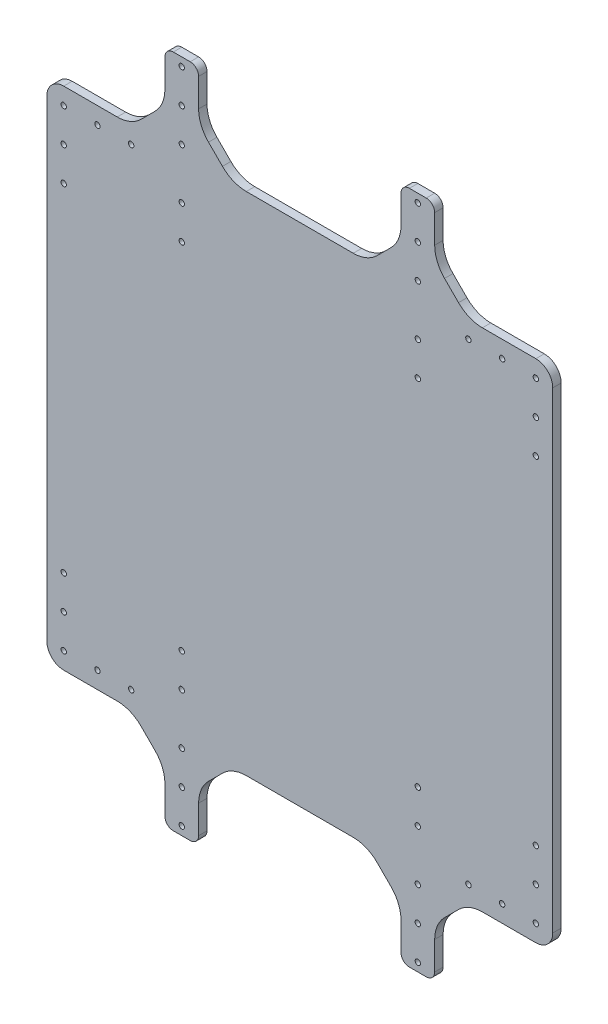
SolidWorks part; units mm, degrees
material "Thornel Mat VMA"
ref_plane "前视基准面" through (0, 0, 0) normal (0, 0, 1) x (1, 0, 0)
ref_plane "上视基准面" through (0, 0, 0) normal (0, 1, 0) x (1, 0, 0)
ref_plane "右视基准面" through (0, 0, 0) normal (1, 0, 0) x (0, 0, -1)
other "Configuration Table"
sketch "草图1" plane through (0, 0, 0) normal (0, 0, 1) x (1, 0, 0)
  line L1 (0, 0) -> (300, 0)
  line L2 (0, 0) -> (0, 300)
  line L3 (0, 300) -> (300, 300)
  line L4 (300, 0) -> (300, 300)
  dimension "D1" = 300
  dimension "D2" = 300
extrude "凸台-拉伸1" add sketch "草图1" along normal blind 5
sketch "草图2" plane through (0, 0, 5) normal (0, 0, 1) x (1, 0, 0)
  line L0 (300, 300) -> (0, 300) construction
  line L1 (10, 290) -> (290, 290) construction
  line L2 (10, 290) -> (10, 10) construction
  line L3 (10, 10) -> (290, 10) construction
  line L4 (290, 290) -> (290, 10) construction
  line L5 (300, 0) -> (300, 300) construction
  line L6 (0, 0) -> (300, 0) construction
  line L7 (0, 300) -> (0, 0) construction
  circle A0 centre (10, 10) radius 1.6
  circle A1 centre (290, 10) radius 1.6
  circle A2 centre (290, 290) radius 1.6
  circle A3 centre (10, 290) radius 1.6
  circle A4 centre (10, 270) radius 1.6
  circle A5 centre (10, 250) radius 1.6
  circle A6 centre (10, 30) radius 1.6
  circle A7 centre (10, 50) radius 1.6
  circle A8 centre (30, 290) radius 1.6
  circle A9 centre (50, 290) radius 1.6
  circle A10 centre (270, 290) radius 1.6
  circle A11 centre (250, 290) radius 1.6
  circle A12 centre (290, 270) radius 1.6
  circle A13 centre (290, 250) radius 1.6
  circle A14 centre (290, 30) radius 1.6
  circle A15 centre (290, 50) radius 1.6
  circle A16 centre (270, 10) radius 1.6
  circle A17 centre (250, 10) radius 1.6
  circle A18 centre (30, 10) radius 1.6
  circle A19 centre (50, 10) radius 1.6
  dimension "D5" = 3.2
  dimension "D6" = 20
  dimension "D7" = 20
  dimension "D8" = 20
  dimension "D9" = 20
  dimension "D10" = 20
  dimension "D11" = 20
  dimension "D12" = 20
  dimension "D13" = 20
  dimension "D14" = 20
  dimension "D15" = 20
  dimension "D16" = 20
  dimension "D17" = 20
  dimension "D18" = 20
  dimension "D19" = 20
  dimension "D20" = 20
  dimension "D21" = 20
  dimension "D1" = 10
  dimension "D2" = 10
  dimension "D3" = 10
  dimension "D4" = 10
extrude "切除-拉伸1" cut sketch "草图2" against normal blind 5
sketch "草图3" plane through (0, 0, 5) normal (0, 0, 1) x (1, 0, 0)
  line L0 (150, 300) -> (150, 0) construction
  line L1 (300, 300) -> (0, 300) construction
  line L2 (0, 0) -> (300, 0) construction
  line L3 (0, 300) -> (0, 0) construction
  line L4 (70, 0) -> (90, 0)
  line L5 (70, 0) -> (70, -50)
  line L6 (70, -50) -> (90, -50)
  line L7 (90, 0) -> (90, -50)
  line L8 (0, 150) -> (300, 150) construction
  line L9 (300, 0) -> (300, 300) construction
  line L10 (90, 300) -> (90, 350)
  line L11 (70, 350) -> (90, 350)
  line L12 (70, 300) -> (70, 350)
  line L13 (70, 300) -> (90, 300)
  line L14 (230, 300) -> (210, 300)
  line L15 (230, 300) -> (230, 350)
  line L16 (230, 350) -> (210, 350)
  line L17 (210, 300) -> (210, 350)
  line L18 (210, 0) -> (210, -50)
  line L19 (230, -50) -> (210, -50)
  line L20 (230, 0) -> (230, -50)
  line L21 (230, 0) -> (210, 0)
  dimension "D1" = 20
  dimension "D2" = 70
  dimension "D3" = 50
extrude "凸台-拉伸2" add sketch "草图3" against normal through all
sketch "草图5" plane through (0, 0, 5) normal (0, 0, 1) x (1, 0, 0)
  line L0 (80, 350) -> (80, 250) construction
  line L1 (90, 350) -> (70, 350) construction
  line L2 (150, 300) -> (150, 150) construction
  line L3 (210, 300) -> (90, 300) construction
  line L4 (0, 150) -> (150, 150) construction
  line L5 (0, 300) -> (0, 0) construction
  line L6 (80, -50) -> (80, 50) construction
  line L7 (220, -50) -> (220, 50) construction
  line L8 (220, 350) -> (220, 250) construction
  circle A0 centre (80, 345) radius 1.6
  circle A1 centre (80, 325) radius 1.6
  circle A2 centre (80, 305) radius 1.6
  circle A3 centre (80, 255) radius 1.6
  circle A4 centre (80, 275) radius 1.6
  circle A5 centre (80, 25) radius 1.6
  circle A6 centre (80, 45) radius 1.6
  circle A7 centre (80, -5) radius 1.6
  circle A8 centre (80, -25) radius 1.6
  circle A9 centre (80, -45) radius 1.6
  circle A10 centre (220, -45) radius 1.6
  circle A11 centre (220, -25) radius 1.6
  circle A12 centre (220, -5) radius 1.6
  circle A13 centre (220, 45) radius 1.6
  circle A14 centre (220, 25) radius 1.6
  circle A15 centre (220, 275) radius 1.6
  circle A16 centre (220, 255) radius 1.6
  circle A17 centre (220, 305) radius 1.6
  circle A18 centre (220, 325) radius 1.6
  circle A19 centre (220, 345) radius 1.6
  dimension "D2" = 3.2
  dimension "D3" = 5
  dimension "D4" = 20
  dimension "D5" = 20
  dimension "D6" = 5
  dimension "D7" = 20
  dimension "D1" = 100
extrude "切除-拉伸2" cut sketch "草图5" against normal through all
chamfer "倒角1" distance 20 angle 45 8 edges at (230, 0, 2.5) (210, 0, 2.5) (90, 0, 2.5) (70, 0, 2.5) (230, 300, 2.5) (210, 300, 2.5) (90, 300, 2.5) (70, 300, 2.5)
fillet "圆角1" radius 20 16 edges at (50, 0, 2.5) (70, -20, 2.5) (90, -20, 2.5) (110, 0, 2.5) (190, 0, 2.5) (210, -20, 2.5) (230, -20, 2.5) (250, 0, 2.5) (250, 300, 2.5) (230, 320, 2.5) (210, 320, 2.5) (190, 300, 2.5) (110, 300, 2.5) (90, 320, 2.5) (70, 320, 2.5) (50, 300, 2.5)
fillet "圆角2" radius 5 8 edges at (230, -50, 2.5) (210, -50, 2.5) (230, 350, 2.5) (70, 350, 2.5) (90, 350, 2.5) (70, -50, 2.5) (90, -50, 2.5) (210, 350, 2.5)
fillet "圆角3" radius 10 4 edges at (0, 0, 2.5) (0, 300, 2.5) (300, 0, 2.5) (300, 300, 2.5)
